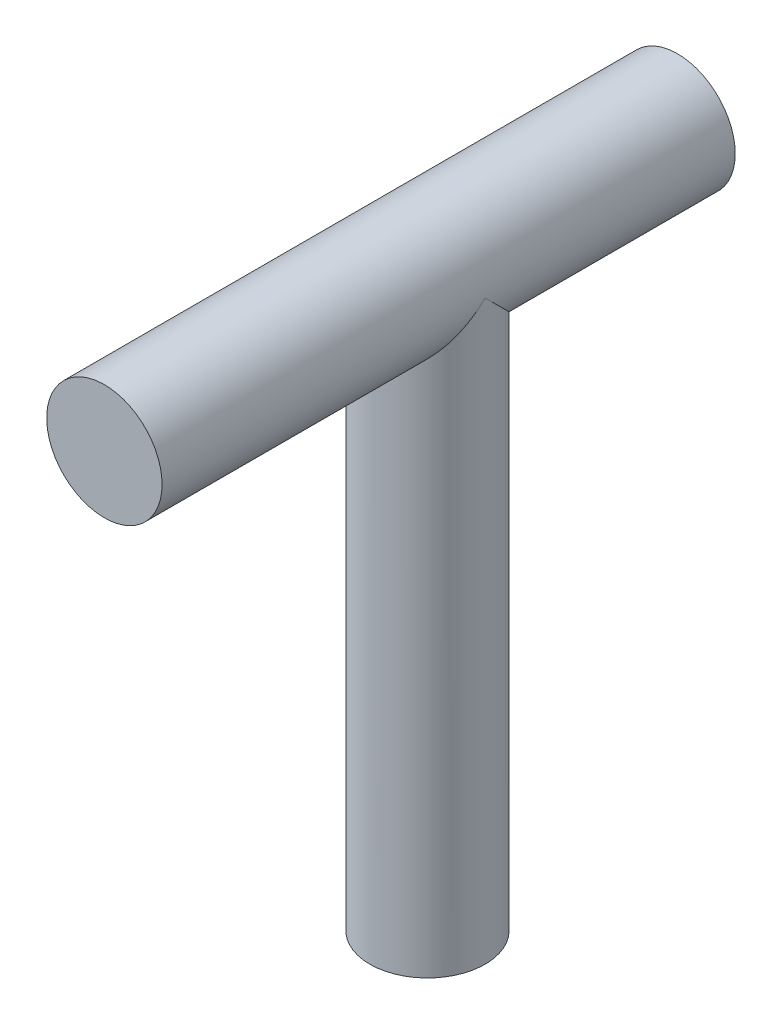
SolidWorks part; units mm, degrees
ref_plane "Спереди" through (0, 0, 0) normal (0, 0, 1) x (1, 0, 0)
ref_plane "Сверху" through (0, 0, 0) normal (0, 1, 0) x (1, 0, 0)
ref_plane "Справа" through (0, 0, 0) normal (1, 0, 0) x (0, 0, -1)
sketch "Эскиз2" plane through (0, 0, 0) normal (0, 1, 0) x (1, 0, 0)
  circle A0 centre (0, 0) radius 15
  dimension "D1" = 30
extrude "Бобышка-Вытянуть1" add sketch "Эскиз2" along normal blind 150
sketch "Эскиз3" plane through (0, 0, 0) normal (0, 0, 1) x (1, 0, 0)
  line L0 (15, 150) -> (-15, 150) construction
  circle A0 centre (0, 150) radius 15
  point P4 (15, 150)
extrude "Бобышка-Вытянуть2" add sketch "Эскиз3" along normal blind 84 and the other way blind 65
